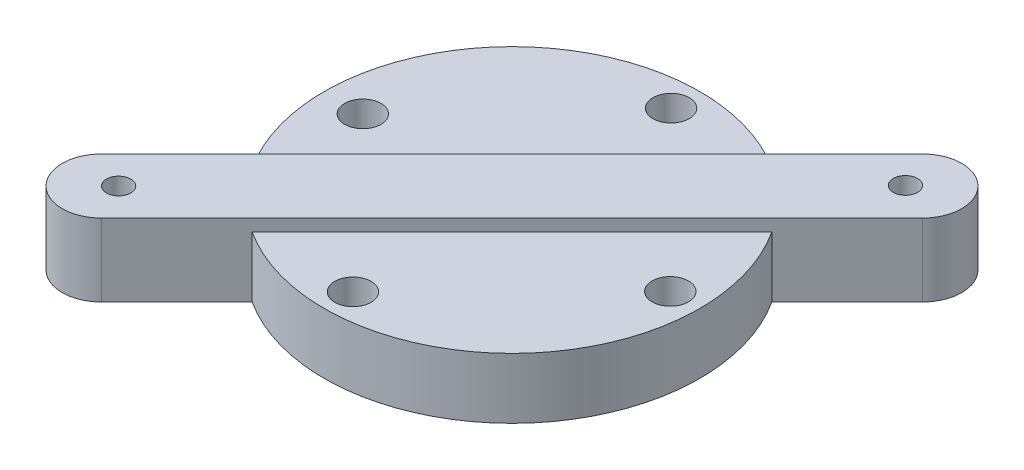
SolidWorks part; units mm, degrees
ref_plane "Front Plane" through (0, 0, 0) normal (0, 0, 1) x (1, 0, 0)
ref_plane "Top Plane" through (0, 0, 0) normal (0, 1, 0) x (1, 0, 0)
ref_plane "Right Plane" through (0, 0, 0) normal (1, 0, 0) x (0, 0, -1)
sketch "Sketch6" plane through (0, 0, 0) normal (0, 1, 0) x (1, 0, 0)
  circle A0 centre (0, 0) radius 31
extrude "Boss-Extrude3" add sketch "Sketch6" along normal blind 10
sketch "Sketch7" plane through (0, 0, 0) normal (0, 1, 0) x (1, 0, 0)
  circle A0 centre (0, 26.2486) radius 3
  circle A1 centre (26.123, 0) radius 3
  circle A2 centre (-24.6159, 0) radius 3
  circle A3 centre (0, -26.2486) radius 3
extrude "Cut-Extrude4" cut sketch "Sketch7" along normal blind 10
sketch "Sketch8" plane through (0, 0, 0) normal (0, 1, 0) x (1, 0, 0)
  line L0 (-33.8704, -33.8704) -> (33.8704, 33.8704) construction
  line L1 (-38.449, -29.2918) -> (29.2918, 38.449)
  line L2 (-29.2918, -38.449) -> (38.449, 29.2918)
  arc A0 (-38.449, -29.2918) -> (-29.2918, -38.449) centre (-33.8704, -33.8704) ccw
  arc A1 (38.449, 29.2918) -> (29.2918, 38.449) centre (33.8704, 33.8704) ccw
  circle A4 centre (32.3762, 32.5409) radius 2
  circle A5 centre (-32.4562, -32.4562) radius 2
  point P3 (0, 0)
  point P10 (-32.4562, -32.4562)
  point P18 (32.3762, 32.5409)
extrude "Boss-Extrude8" add sketch "Sketch8" along normal blind 12
